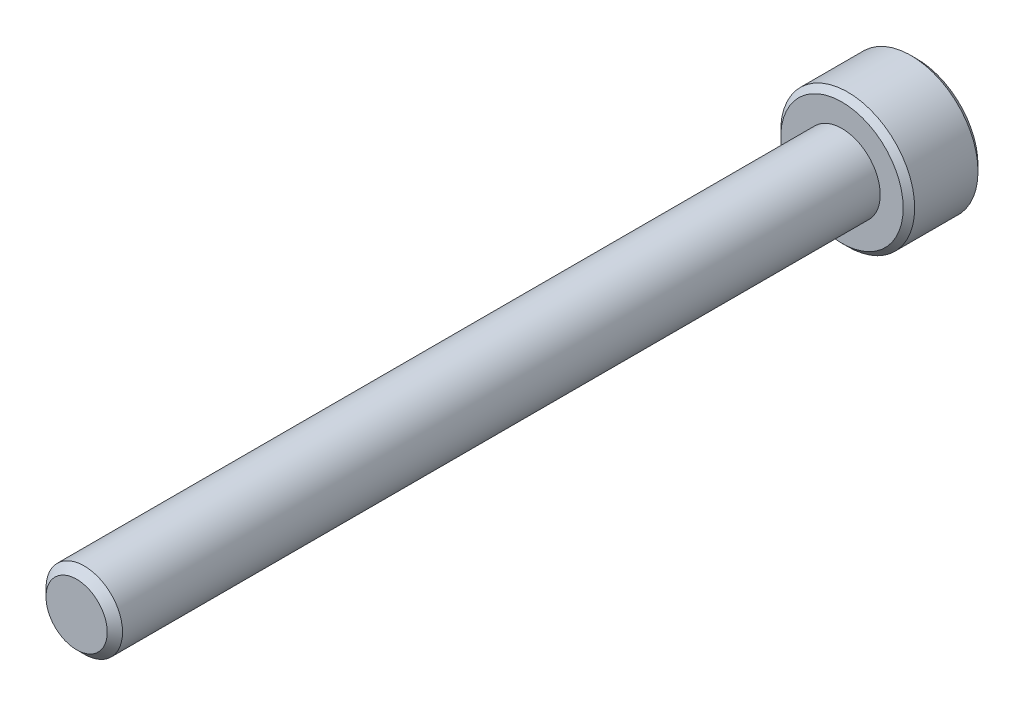
SolidWorks part; units mm, degrees
material "AISI 304"
ref_plane "前视基准面" through (0, 0, 0) normal (0, 0, 1) x (1, 0, 0)
ref_plane "上视基准面" through (0, 0, 0) normal (0, 1, 0) x (1, 0, 0)
ref_plane "右视基准面" through (0, 0, 0) normal (1, 0, 0) x (0, 0, -1)
sketch "草图1" plane through (0, 0, 0) normal (0, 0, 1) x (1, 0, 0)
  circle A0 centre (0, 0) radius 3.5
  dimension "D1" = 7
extrude "凸台-拉伸1" add sketch "草图1" along normal blind 3.91
sketch "草图2" plane through (0, 0, 3.91) normal (0, 0, 1) x (1, 0, 0)
  circle A0 centre (0, 0) radius 2
  dimension "D1" = 4
extrude "凸台-拉伸2" add sketch "草图2" along normal blind 40
sketch "草图3" plane through (0, 0, 0) normal (0, 0, -1) x (-1, 0, 0)
  line L1 (0, 1.7609) -> (-1.525, 0.8805)
  line L2 (-1.525, 0.8805) -> (-1.525, -0.8805)
  line L3 (-1.525, -0.8805) -> (0, -1.7609)
  line L4 (0, -1.7609) -> (1.525, -0.8805)
  line L5 (1.525, -0.8805) -> (1.525, 0.8805)
  line L6 (1.525, 0.8805) -> (0, 1.7609)
  circle A0 centre (0, 0) radius 1.525 construction
  dimension "D1" = 3.05
extrude "切除-拉伸1" cut sketch "草图3" against normal blind 2
chamfer "倒角1" distance 0.4 angle 45 1 edges at (2, 0, 43.91)
chamfer "倒角2" distance 0.3 angle 45 2 edges at (3.5, 0, 3.91) (3.5, 0, 0)
